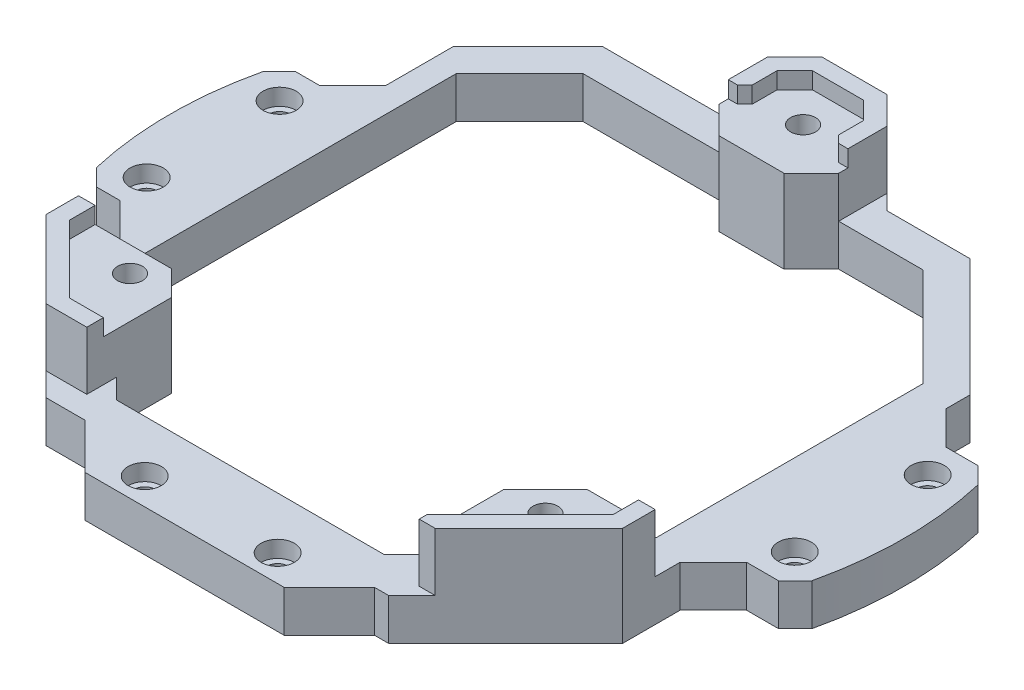
SolidWorks part; units mm, degrees
ref_plane "Спереди" through (0, 0, 0) normal (0, 0, 1) x (1, 0, 0)
ref_plane "Сверху" through (0, 0, 0) normal (0, 1, 0) x (1, 0, 0)
ref_plane "Справа" through (0, 0, 0) normal (1, 0, 0) x (0, 0, -1)
sketch "Эскиз2" plane through (0, 0, 0) normal (0, 1, 0) x (1, 0, 0)
  line L0 (3, 36) -> (-3, 36) construction
  line L1 (3, 36) -> (-3, 36) construction
  line L2 (0, 32) -> (5, 32) construction
  line L3 (5, 31) -> (5, 34) construction
  line L4 (-3.0828, 27.8) -> (-5.2, 29.9172)
  line L5 (5, 34) -> (3, 36) construction
  line L6 (-5, 34) -> (-5, 31) construction
  line L7 (-3, 36) -> (-5, 34) construction
  line L8 (5, 31) -> (5, 34) construction
  line L9 (5, 34) -> (3, 36) construction
  line L10 (-5, 34) -> (-5, 31) construction
  line L11 (-3, 36) -> (-5, 34) construction
  line L12 (5.2, 31) -> (5.2, 34.0828)
  line L13 (5.2, 34.0828) -> (3.0828, 36.2)
  line L14 (3.0828, 36.2) -> (-3.0828, 36.2)
  line L15 (-3.0828, 36.2) -> (-5.2, 34.0828)
  line L16 (-5.2, 34.0828) -> (-5.2, 31)
  line L17 (7.2, 31) -> (7.2, 34.9113)
  line L18 (7.2, 34.9113) -> (3.9113, 38.2)
  line L19 (3.9113, 38.2) -> (-3.9113, 38.2)
  line L20 (-3.9113, 38.2) -> (-7.2, 34.9113)
  line L21 (-7.2, 34.9113) -> (-7.2, 31)
  line L22 (-3.9113, 25.8) -> (-7.2, 29.0887)
  line L23 (5.2, 29.9172) -> (3.0828, 27.8)
  line L24 (3.0828, 27.8) -> (-3.0828, 27.8)
  line L25 (3.9113, 25.8) -> (-3.9113, 25.8)
  line L26 (7.2, 29.0887) -> (3.9113, 25.8)
  line L27 (-5.2, 31) -> (-5.2, 29.9172)
  line L28 (-7.2, 31) -> (-7.2, 29.0887)
  line L29 (5.2, 29.9172) -> (5.2, 31)
  line L30 (7.2, 29.0887) -> (7.2, 31)
  line L33 (20, -33) -> (20, -24)
  line L34 (20, -24) -> (25, -19)
  line L35 (25, -19) -> (31, -19)
  line L36 (31, -22) -> (31, 25) construction
  line L38 (18, -35) -> (31, -22) construction
  line L39 (20, -33) -> (31, -22) construction
  line L40 (21.9113, -34.2) -> (33.2, -22.9113)
  line L41 (20.1414, -33.1414) -> (31.2, -22.0828) construction
  line L43 (31.2, -22.0828) -> (31.2, -19) construction
  line L44 (20.1414, -33.1414) -> (31.1414, -22.1414) construction
  line L45 (33.2, -22.9113) -> (33.2, -19)
  line L46 (20, -33) -> (20.1414, -33.1414)
  line L47 (31, -19) -> (33.2, -19)
  line L48 (-20, -32) -> (-20, -24)
  line L49 (-24, -32) -> (-10, -32) construction
  line L50 (-20, -24) -> (-23, -21)
  line L51 (-23, -21) -> (-32, -21)
  line L52 (-32, 22) -> (-32, -24) construction
  line L53 (-32, -24) -> (-24, -32) construction
  line L54 (-32, -21) -> (-32, -24) construction
  line L55 (-24, -32) -> (-20, -32) construction
  line L56 (-32, -24) -> (-24, -32) construction
  line L57 (-32, 22) -> (-32, -21) construction
  line L58 (-20, -32) -> (-10, -32) construction
  line L59 (-34.2, -21) -> (-34.2, -24.9113)
  line L60 (-34.2, -24.9113) -> (-24.9113, -34.2)
  line L61 (-24.9113, -34.2) -> (-20, -34.2)
  line L62 (-34.2, -21) -> (-32, -21)
  line L63 (-20, -34.2) -> (-20, -32)
  line L64 (-1020, -34.2) -> (48980, -34.2) construction
  line L65 (20, -33) -> (20, -34.2)
  line L66 (20, -34.2) -> (21.9113, -34.2)
  line L68 (21.5556, -34.5556) -> (33.2, -22.9113) construction
  circle A0 centre (25, -24) radius 1.25 construction
  circle A1 centre (0, 32) radius 1.25 construction
  circle A2 centre (-25, -24) radius 1.25 construction
  circle A3 centre (25, -24) radius 1.25 construction
  circle A4 centre (0, 32) radius 1.25 construction
  circle A5 centre (-25, -24) radius 1.25 construction
  circle A6 centre (-25, -24) radius 1.5
  circle A7 centre (25, -24) radius 1.5
  circle A8 centre (0, 32) radius 1.5
  dimension "D1" = 3
  dimension "D4" = 5
  dimension "D5" = 5
  dimension "D7" = 0.2
  dimension "D9" = 5
  dimension "D10" = 3
  dimension "D2" = 0.2
  dimension "D3" = 2
  dimension "D6" = 0.2
  dimension "D8" = 2
  dimension "D11" = 2.2
extrude "Бобышка-Вытянуть2" add sketch "Эскиз2" against normal blind 5 contours L61 L63 L48 L50 L51 L62 L59 L60 A6 | L47 L35 L34 L33 L46 L40 L45 A7 | L26 L30 L17 L18 L19 L20 L21 L28 L22 L25 L29 L23 L24 L4 L27 L16 L15 L14 L13 L12 | L23 L29 L12 L13 L14 L15 L16 L27 L4 L24 A8
sketch "Эскиз3" plane through (0, 0, 0) normal (0, 1, 0) x (1, 0, 0)
  line L11 (-24, -32) -> (-10, -32) construction
  line L12 (7.2, 29.0887) -> (7.2, 34.9113) construction
  line L15 (7.2, 34.9113) -> (3.9113, 38.2) construction
  line L22 (-32, -24) -> (-24, -32) construction
  line L23 (-32, 22) -> (-32, -24) construction
  line L24 (3.9113, 38.2) -> (-3.9113, 38.2) construction
  line L25 (-7.2, 34.9113) -> (-7.2, 29.0887) construction
  line L34 (-3.9113, 38.2) -> (-7.2, 34.9113) construction
  line L35 (7.2, 30.2) -> (7.2, 34.9113)
  line L36 (7.2, 34.9113) -> (3.9113, 38.2)
  line L37 (3.9113, 38.2) -> (-3.9113, 38.2)
  line L38 (-7.2, 34.9113) -> (-7.2, 30.2)
  line L39 (-3.9113, 38.2) -> (-7.2, 34.9113)
  line L40 (26, 30) -> (6, 30) construction
  line L41 (-24, -32) -> (-20, -32) construction
  line L42 (-32, -24) -> (-24, -32) construction
  line L43 (-32, -21) -> (-32, -24) construction
  line L44 (-24.9113, -34.2) -> (-20, -34.2)
  line L45 (-20, -34.2) -> (-20, -24)
  line L46 (-20, -24) -> (-23, -21)
  line L47 (-23, -21) -> (-34.2, -21)
  line L55 (6, 30) -> (5, 31) construction
  line L56 (-34.2, -21) -> (-34.2, -24.9113)
  line L57 (5, 31) -> (5, 34) construction
  line L58 (-34.2, -24.9113) -> (-24.9113, -34.2)
  line L59 (-24.9113, -34.2) -> (-20, -34.2)
  line L60 (-20, -34.2) -> (-20, -32.2)
  line L61 (-20, -24) -> (-23, -21) construction
  line L62 (-32.2, -21) -> (-34.2, -21)
  line L65 (-34.2, -21) -> (-34.2, -24.9113)
  line L66 (-34.2, -24.9113) -> (-24.9113, -34.2)
  line L67 (-32, 22) -> (-32, -21) construction
  line L68 (-23, -21) -> (-32, -21) construction
  line L69 (-20, -32) -> (-20, -24) construction
  line L70 (-20, -32) -> (-10, -32) construction
  line L71 (-32.2, -21) -> (-32.2, -24.0828)
  line L72 (-32.2, -24.0828) -> (-24.0828, -32.2)
  line L73 (-24.0828, -32.2) -> (-20, -32.2)
  line L74 (-20, -32.2) -> (-20, -32) construction
  line L75 (5, 34) -> (3, 36) construction
  line L77 (-32, -21) -> (-32.2, -21) construction
  line L100 (3, 36) -> (-3, 36) construction
  line L101 (-3, 36) -> (-5, 34) construction
  line L102 (-5, 34) -> (-5, 31) construction
  line L103 (-5, 31) -> (-6, 30) construction
  line L104 (-6, 30) -> (-15, 30) construction
  line L105 (7.2, 30) -> (6, 30) construction
  line L106 (6, 30) -> (5, 31) construction
  line L107 (5, 31) -> (5, 34) construction
  line L108 (5, 34) -> (3, 36) construction
  line L109 (3, 36) -> (-3, 36) construction
  line L110 (-3, 36) -> (-5, 34) construction
  line L111 (-5, 34) -> (-5, 31) construction
  line L112 (-5, 31) -> (-6, 30) construction
  line L113 (-6, 30) -> (-7.2, 30) construction
  line L117 (7.2, 29.0887) -> (7.2, 30) construction
  line L118 (7.2, 30.2) -> (6.0828, 30.2)
  line L119 (6.0828, 30.2) -> (5.2, 31.0828)
  line L120 (5.2, 31.0828) -> (5.2, 34.0828)
  line L121 (5.2, 34.0828) -> (3.0828, 36.2)
  line L122 (3.0828, 36.2) -> (-3.0828, 36.2)
  line L123 (-3.0828, 36.2) -> (-5.2, 34.0828)
  line L124 (-5.2, 34.0828) -> (-5.2, 31.0828)
  line L125 (-5.2, 31.0828) -> (-6.0828, 30.2)
  line L126 (-6.0828, 30.2) -> (-7.2, 30.2)
  line L127 (-7.2, 30.2) -> (-7.2, 30) construction
  line L128 (7.2, 30) -> (7.2, 30.2) construction
  dimension "D1" = 0
  dimension "D2" = 0.2
  dimension "D5" = 0.2
extrude "Бобышка-Вытянуть5" add sketch "Эскиз3" along normal blind 2
sketch "Эскиз5" plane through (0, 0, 0) normal (0, 1, 0) x (1, 0, 0)
  line L0 (25, -19) -> (33.2, -19) construction
  line L1 (31, -22) -> (31, 25) construction
  line L2 (31.2, -19) -> (33.2, -19)
  line L10 (20, -24) -> (20, -34.2) construction
  line L11 (20, -34.2) -> (21.9113, -34.2) construction
  line L12 (21.9113, -34.2) -> (33.2, -22.9113) construction
  line L13 (33.2, -22.9113) -> (33.2, -19) construction
  line L14 (31, -22) -> (31, -19) construction
  line L15 (20, -33.2828) -> (20, -34.2)
  line L16 (20, -34.2) -> (21.9113, -34.2)
  line L17 (21.9113, -34.2) -> (33.2, -22.9113)
  line L18 (33.2, -22.9113) -> (33.2, -19)
  line L19 (20, -33.2828) -> (31.2, -22.0828)
  line L20 (18, -35) -> (31, -22) construction
  line L21 (20, -33) -> (31, -22) construction
  line L22 (31.2, -22.0828) -> (31.2, -19)
  line L23 (18.1414, -35.1414) -> (31.2, -22.0828) construction
  line L24 (18, -35) -> (31, -22) construction
  line L25 (20, -33) -> (20, -33.2828) construction
  line L26 (31, -19) -> (31.2, -19) construction
  dimension "D1" = 0.2
extrude "Бобышка-Вытянуть6" add sketch "Эскиз5" along normal up to surface (2 mm away) up to face at (-27.7243, 2, 27.9743)
sketch "Эскиз6" plane through (0, -5, 0) normal (0, -1, 0) x (1, 0, 0)
  line L0 (7.2, -29.0887) -> (3.9113, -25.8) construction
  line L1 (3.9113, -25.8) -> (-3.9113, -25.8) construction
  line L2 (-3.9113, -25.8) -> (-7.2, -29.0887) construction
  line L3 (-7.2, -29.0887) -> (-7.2, -34.9113) construction
  line L4 (-7.2, -34.9113) -> (-3.9113, -38.2) construction
  line L5 (-3.9113, -38.2) -> (3.9113, -38.2) construction
  line L6 (3.9113, -38.2) -> (7.2, -34.9113) construction
  line L7 (7.2, -34.9113) -> (7.2, -29.0887) construction
  line L8 (20, 34.2) -> (20, 24) construction
  line L9 (20, 24) -> (25, 19) construction
  line L10 (25, 19) -> (33.2, 19) construction
  line L11 (33.2, 19) -> (33.2, 22.9113) construction
  line L12 (33.2, 22.9113) -> (21.9113, 34.2) construction
  line L13 (21.9113, 34.2) -> (20, 34.2) construction
  line L14 (-20, 34.2) -> (-24.9113, 34.2) construction
  line L15 (-24.9113, 34.2) -> (-34.2, 24.9113) construction
  line L16 (-34.2, 24.9113) -> (-34.2, 21) construction
  line L17 (-34.2, 21) -> (-23, 21) construction
  line L18 (-23, 21) -> (-20, 24) construction
  line L19 (-20, 24) -> (-20, 34.2) construction
  line L20 (7.2, -29.0887) -> (3.9113, -25.8)
  line L21 (3.9113, -25.8) -> (-3.9113, -25.8)
  line L22 (-3.9113, -25.8) -> (-7.2, -29.0887)
  line L23 (-7.2, -33.0887) -> (-7.2, -34.9113) construction
  line L24 (-7.2, -34.9113) -> (-3.9113, -38.2)
  line L25 (-3.9113, -38.2) -> (3.9113, -38.2)
  line L26 (3.9113, -38.2) -> (7.2, -34.9113)
  line L27 (7.2, -34.9113) -> (7.2, -29.0887) construction
  line L28 (20, 27.626) -> (20, 24)
  line L29 (20, 24) -> (25, 19)
  line L30 (25, 19) -> (29.2, 19) construction
  line L31 (33.2, 19) -> (33.2, 22.9113)
  line L32 (33.2, 22.9113) -> (21.9113, 34.2)
  line L33 (21.9113, 34.2) -> (20, 34.2) construction
  line L34 (-20, 34.2) -> (-24.9113, 34.2) construction
  line L35 (-24.9113, 34.2) -> (-34.2, 24.9113)
  line L36 (-34.2, 24.9113) -> (-34.2, 21)
  line L37 (-29.626, 21) -> (-23, 21)
  line L38 (-23, 21) -> (-20, 24)
  line L39 (-20, 24) -> (-20, 30.626)
  line L40 (-8, 37) -> (13, 37) construction
  line L41 (-8, 37) -> (13, 37)
  line L42 (21.9113, 34.2) -> (19.1113, 37)
  line L43 (19.1113, 37) -> (13, 37)
  line L44 (-8, 37) -> (-22.1113, 37)
  line L45 (-22.1113, 37) -> (-24.9113, 34.2)
  line L46 (-20, 30.626) -> (-17.626, 33)
  line L47 (-17.626, 33) -> (14.626, 33)
  line L48 (14.626, 33) -> (20, 27.626)
  line L49 (-34.2, 21) -> (-34.2, -24.0887)
  line L50 (-34.2, -24.0887) -> (-25.2, -33.0887)
  line L51 (-31.2, 19.426) -> (-31.2, -21.4319)
  line L52 (-31.2, 21) -> (-29.626, 21) construction
  line L53 (-31.2, -21.4319) -> (-23.5431, -29.0887)
  line L54 (-23.5431, -29.0887) -> (-7.2, -29.0887)
  line L55 (-25.2, -33.0887) -> (-9.0225, -33.0887)
  line L56 (-7.2, -34.9113) -> (-9.0225, -33.0887)
  line L57 (-9.0225, -33.0887) -> (-7.2, -33.0887) construction
  line L58 (-7.2, -29.0887) -> (-7.2, -33.0887) construction
  line L59 (-34.2, 21) -> (-31.2, 21) construction
  line L60 (-20, 30.626) -> (-20, 34.2) construction
  line L61 (-31.2, 19.426) -> (-29.626, 21)
  line L62 (-31.2, 21) -> (-31.2, 19.426) construction
  line L63 (20, 34.2) -> (20, 27.626) construction
  line L64 (33.2, 19) -> (33.2, -18.9113)
  line L65 (33.2, -18.9113) -> (19.0225, -33.0887)
  line L66 (19.0225, -33.0887) -> (9.0225, -33.0887)
  line L67 (9.0225, -33.0887) -> (7.2, -34.9113)
  line L68 (7.2, -29.0887) -> (17.3657, -29.0887)
  line L69 (17.3657, -29.0887) -> (29.2, -17.2544)
  line L70 (29.2, -17.2544) -> (29.2, 14.8)
  line L71 (25, 19) -> (29.2, 14.8)
  line L72 (29.2, 19) -> (33.2, 19) construction
  line L73 (29.2, 14.8) -> (29.2, 19) construction
  circle A0 centre (0, 0) radius 44.5 construction
  dimension "D7" = 89
  dimension "D1" = 4
  dimension "D2" = 6
  dimension "D3" = 6
  dimension "D4" = 3
  dimension "D5" = 4
  dimension "D6" = 4
  dimension "D8" = 18
  dimension "D9" = 6
  dimension "D10" = 4
  dimension "D11" = 10
  dimension "D12" = 4
extrude "Бобышка-Вытянуть7" add sketch "Эскиз6" along normal blind 5
sketch "Эскиз11" plane through (0, -5, 0) normal (0, 1, 0) x (1, 0, 0)
  line L0 (-1000, 0) -> (49000, 0) construction
  line L1 (0, -1000) -> (0, 49000) construction
  line L2 (39, -1000) -> (39, 49000) construction
  line L3 (-1000, -39.23) -> (49000, -39.23) construction
  line L4 (41.0539, 12) -> (33.2, 12)
  line L5 (33.2, 18.9113) -> (33.2, -19) construction
  line L6 (41.0539, -12) -> (33.2, -12)
  line L7 (41.0539, 12) -> (43.0539, 10)
  line L8 (41.0539, -12) -> (43.0539, -10)
  line L9 (42.5399, -12) -> (41.0539, -12) construction
  line L10 (42.5399, 12) -> (41.0539, 12) construction
  line L11 (33.2, 12) -> (33.2, -12)
  line L12 (33.2, 18.9113) -> (33.2, 12) construction
  line L13 (33.2, -12) -> (33.2, -19) construction
  line L14 (-41.0539, 12) -> (-34.2, 12)
  line L15 (-41.0539, 12) -> (-43.0539, 10)
  line L16 (-41.0539, -12) -> (-43.0539, -10)
  line L17 (-33.2, 0) -> (-33.2, -12) construction
  line L18 (-41.0539, -12) -> (-34.2, -12)
  line L19 (-34.2, -21) -> (-34.2, 24.0887) construction
  line L20 (-34.2, -12) -> (-34.2, 12)
  line L21 (-34.2, 12) -> (-34.2, 24.0887) construction
  line L22 (-34.2, 12) -> (-33.2, 12) construction
  line L23 (-33.2, 12) -> (-33.2, 0) construction
  line L24 (-34.2, -12) -> (-33.2, -12) construction
  line L25 (-34.2, -21) -> (-34.2, -12) construction
  line L26 (-12, -42.44) -> (12, -42.44)
  line L27 (12, -42.44) -> (17.44, -37)
  line L28 (19.1113, -37) -> (-22.1113, -37) construction
  line L29 (-12, -42.44) -> (-17.44, -37)
  line L30 (17.44, -37) -> (-17.44, -37)
  line L31 (-17.44, -37) -> (-22.1113, -37) construction
  circle A0 centre (39, 8) radius 1.25
  circle A1 centre (39, -8) radius 1.25
  circle A2 centre (-39, 8) radius 1.25
  circle A3 centre (-39, -8) radius 1.25
  circle A4 centre (8, -39.23) radius 1.25
  circle A5 centre (-8, -39.23) radius 1.25
  arc A6 (43.0539, 10) -> (43.0539, -10) centre (0, 0) cw
  arc A7 (43.0539, -10) -> (42.5399, -12) centre (0, 0) cw construction
  arc A8 (42.5399, 12) -> (43.0539, 10) centre (0, 0) cw construction
  arc A9 (-43.0539, 10) -> (-43.0539, -10) centre (0, 0) ccw
  dimension "D3" = 2.5
  dimension "D6" = 44.2
  dimension "D1" = 39
  dimension "D2" = 16
  dimension "D4" = 39.23
  dimension "D5" = 16
  dimension "D7" = 24
  dimension "D8" = 45
  dimension "D9" = 20
  dimension "D10" = 42.44
  dimension "D11" = 24
  dimension "D12" = 45
extrude "Бобышка-Вытянуть8" add sketch "Эскиз11" against normal up to surface (5 mm away) up to face at (-0.9315, -10, -10.8277)
chamfer "Фаска1" distance 4 angle 45 4 edges at (33.2, -7.5, 12) (33.2, -7.5, -12) (-34.2, -7.5, -12) (-34.2, -7.5, 12)
sketch "Эскиз12" plane through (0, -5, 0) normal (0, 1, 0) x (1, 0, 0)
  circle A0 centre (-8, -39.23) radius 1.25 construction
  circle A1 centre (8, -39.23) radius 1.25 construction
  circle A2 centre (39, -8) radius 1.25 construction
  circle A3 centre (39, 8) radius 1.25 construction
  circle A4 centre (-39, -8) radius 1.25 construction
  circle A5 centre (-39, 8) radius 1.25 construction
  circle A6 centre (-8, -39.23) radius 1.25 construction
  circle A7 centre (8, -39.23) radius 1.25 construction
  circle A8 centre (39, -8) radius 1.25 construction
  circle A9 centre (39, 8) radius 1.25 construction
  circle A10 centre (-39, -8) radius 1.25 construction
  circle A11 centre (-39, 8) radius 1.25 construction
  circle A12 centre (-39, 8) radius 2
  circle A13 centre (-39, -8) radius 2
  circle A14 centre (39, 8) radius 2
  circle A15 centre (39, -8) radius 2
  circle A16 centre (8, -39.23) radius 2
  circle A17 centre (-8, -39.23) radius 2
  dimension "D1" = 4
extrude "Вырез-Вытянуть1" cut sketch "Эскиз12" against normal blind 2
